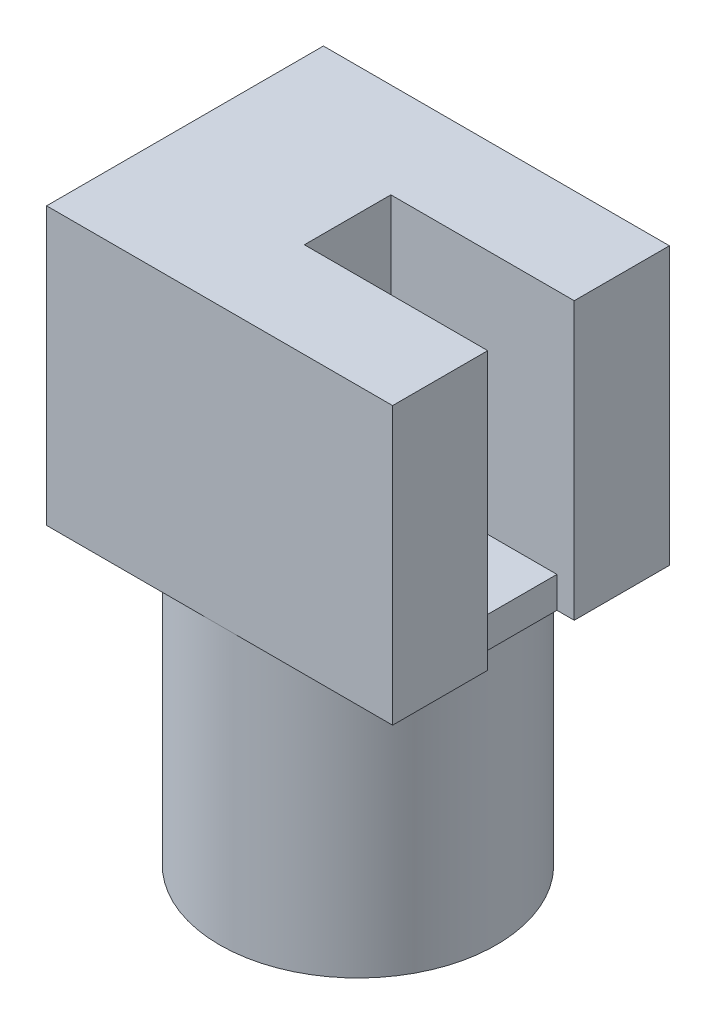
SolidWorks part; units mm, degrees
ref_plane "Front Plane" through (0, 0, 0) normal (0, 0, 1) x (1, 0, 0)
ref_plane "Top Plane" through (0, 0, 0) normal (0, 1, 0) x (1, 0, 0)
ref_plane "Right Plane" through (0, 0, 0) normal (1, 0, 0) x (0, 0, -1)
sketch "Sketch1" plane through (0, 0, 0) normal (0, 1, 0) x (1, 0, 0)
  circle A0 centre (0, 0) radius 20
  dimension "D1" = 40
extrude "Boss-Extrude1" add sketch "Sketch1" along normal blind 40
sketch "Sketch2" plane through (0, 0, 0) normal (0, -1, 0) x (1, 0, 0)
  circle A0 centre (0, 0) radius 2.7
  dimension "D1" = 5.4
extrude "Cut-Extrude1" cut sketch "Sketch2" against normal blind 3.5
sketch "Sketch3" plane through (0, 0, 0) normal (1, 0, 0) x (0, 0, -1)
  line L0 (20, 40) -> (-20, 40) construction
  line L1 (20, 80) -> (-20, 80)
  line L2 (20, 80) -> (20, 40)
  line L3 (20, 40) -> (-20, 40)
  line L4 (-20, 80) -> (-20, 40)
  point P6 (0, 40)
  point P7 (0, 40)
  dimension "D1" = 40
  dimension "D2" = 40
extrude "Boss-Extrude2" add sketch "Sketch3" along normal mid plane 50
sketch "Sketch4" plane through (25, 0, 0) normal (1, 0, 0) x (0, 0, -1)
  line L0 (-20, 40) -> (20, 40) construction
  line L1 (6.25, 80) -> (-6.25, 80)
  line L2 (6.25, 80) -> (6.25, 40)
  line L3 (6.25, 40) -> (-6.25, 40)
  line L4 (-6.25, 80) -> (-6.25, 40)
  line L5 (20, 80) -> (-20, 80) construction
  point P4 (0, 40)
  point P5 (0, 40)
  point P6 (0, 0)
  point P7 (0, 0)
  point P8 (0, 80)
  point P11 (0, 0)
  point P12 (0, 0)
  point P14 (0, 40)
  point P15 (0, 0)
  dimension "D1" = 12.5
extrude "Cut-Extrude2" cut sketch "Sketch4" against normal blind 2.5
sketch "Sketch5" plane through (22.5, 0, 0) normal (1, 0, 0) x (0, 0, -1)
  line L0 (-6.25, 80) -> (-6.25, 40) construction
  line L1 (6.25, 80) -> (-6.25, 80)
  line L2 (6.25, 80) -> (6.25, 44.5)
  line L3 (6.25, 44.5) -> (-6.25, 44.5)
  line L4 (-6.25, 80) -> (-6.25, 44.5)
  dimension "D1" = 4.5
extrude "Cut-Extrude3" cut sketch "Sketch5" against normal blind 24
